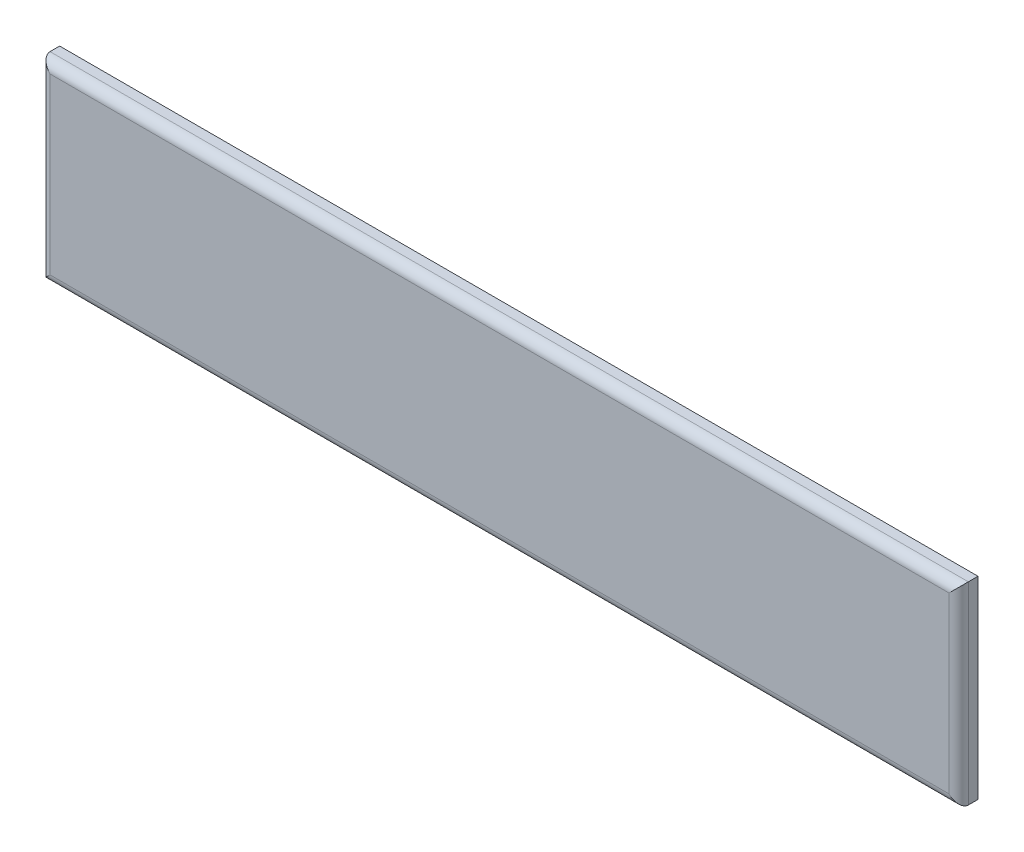
SolidWorks part; units mm, degrees
ref_plane "Front Plane" through (0, 0, 0) normal (0, 0, 1) x (1, 0, 0)
ref_plane "Top Plane" through (0, 0, 0) normal (0, 1, 0) x (1, 0, 0)
ref_plane "Right Plane" through (0, 0, 0) normal (1, 0, 0) x (0, 0, -1)
sketch "Sketch1" plane through (0, 0, 0) normal (0, 0, 1) x (1, 0, 0)
  line L1 (47.5, -10) -> (-47.5, -10)
  line L2 (47.5, -10) -> (47.5, 10)
  line L3 (47.5, 10) -> (-47.5, 10)
  line L4 (-47.5, -10) -> (-47.5, 10)
  line L5 (47.5, -10) -> (-47.5, 10) construction
  line L6 (47.5, 10) -> (-47.5, -10) construction
  point P0 (0, 0)
  dimension "D1" = 95
  dimension "D2" = 20
extrude "Boss-Extrude1" add sketch "Sketch1" along normal mid plane 2
fillet "Fillet1" radius 1 4 edges at (-47.5, 0, 1) (0, -10, 1) (47.5, 0, 1) (0, 10, 1)
hole_wizard "Ø1.0mm Dowel Hole1" positions "Sketch2" profile "Sketch3" hole size "Ø1.0" standard "ANSI Metric"
sketch "Sketch2" plane through (0, 0, -1) normal (0, 0, -1) x (-1, 0, 0)
  line L0 (47.5, -10) -> (-47.5, -10) construction
  line L1 (47.5, 10) -> (47.5, -10) construction
  line L2 (-47.5, -10) -> (-47.5, 10) construction
  point P0 (-44, -8)
  point P2 (-40, -8)
  point P4 (40, -8)
  point P6 (44, -8)
  dimension "D1" = 4
  dimension "D2" = 4
  dimension "D3" = 2
  dimension "D4" = 80
  dimension "D5" = 3.5
  dimension "D6" = 3.5
  dimension "D7" = 2
sketch "Sketch3" plane through (44, -8, -1) normal (1, 0, 0) x (0, 1, 0)
  line L0 (0, 0) -> (0, 1.1502)
  line L1 (0, 1.1502) -> (0.25, 1)
  line L2 (0.25, 1) -> (0.25, 0)
  line L5 (0.25, 0) -> (0, 0)
  line L10 (0, 1.1502) -> (-0.25, 1) construction
  line L11 (0, -6.35) -> (0, 107.95) construction
  dimension "Hole Dia." = 0.5
  dimension "Hole Depth" = 1
  dimension "Drill Angle" = 118
mirror "Mirror1" about plane through (0, 0, 0) normal (0, 1, 0) of "Ø1.0mm Dowel Hole1"
hole_wizard "Ø1.0mm Dowel Hole2" positions "Sketch4" profile "Sketch5" hole size "Ø1.0" standard "ANSI Metric"
sketch "Sketch4" plane through (0, 0, -1) normal (0, 0, -1) x (-1, 0, 0)
  line L0 (-47.5, -10) -> (-47.5, 10) construction
  point P0 (-46.8, 0)
  point P2 (-43.4, 0)
  dimension "D1" = 3.4
  dimension "D2" = 0.7
sketch "Sketch5" plane through (46.8, 0, -1) normal (1, 0, 0) x (0, 1, 0)
  line L0 (0, 0) -> (0, 1.1502)
  line L1 (0, 1.1502) -> (0.25, 1)
  line L2 (0.25, 1) -> (0.25, 0)
  line L5 (0.25, 0) -> (0, 0)
  line L10 (0, 1.1502) -> (-0.25, 1) construction
  line L11 (0, -6.35) -> (0, 107.95) construction
  dimension "Hole Dia." = 0.5
  dimension "Hole Depth" = 1
  dimension "Drill Angle" = 118
mirror "Mirror2" about plane through (0, 0, 0) normal (1, 0, 0) of "Ø1.0mm Dowel Hole2"
